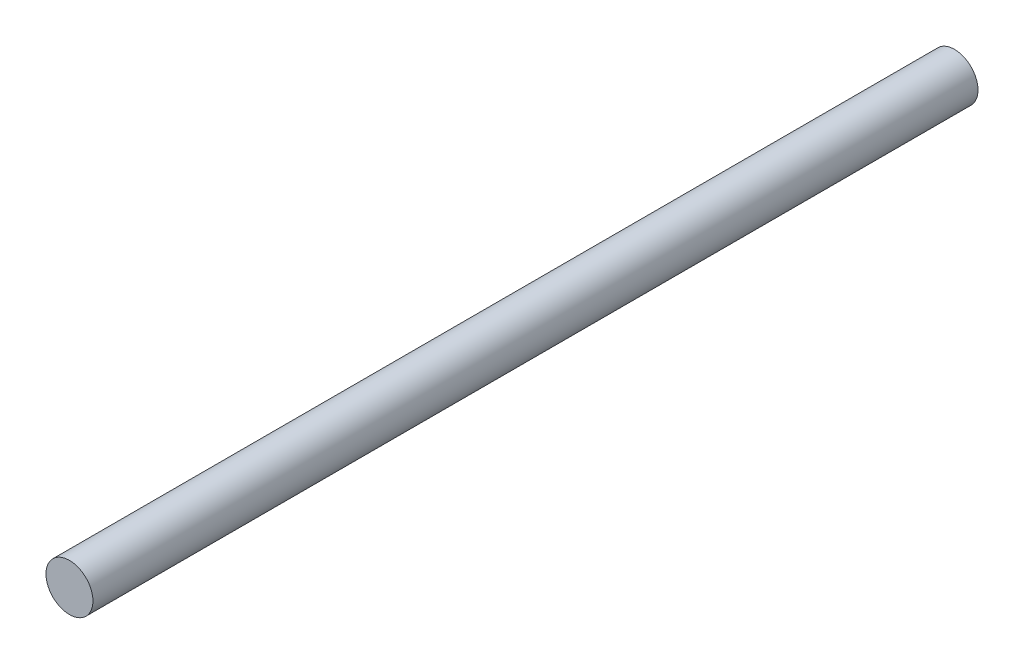
SolidWorks part; units mm, degrees
ref_plane "Front Plane" through (0, 0, 0) normal (0, 0, 1) x (1, 0, 0)
ref_plane "Top Plane" through (0, 0, 0) normal (0, 1, 0) x (1, 0, 0)
ref_plane "Right Plane" through (0, 0, 0) normal (1, 0, 0) x (0, 0, -1)
sketch "Sketch1" plane through (0, 0, 0) normal (0, 0, 1) x (1, 0, 0)
  circle A0 centre (0, 0) radius 11
  dimension "D1" = 22
extrude "Boss-Extrude1" add sketch "Sketch1" along normal blind 414.6
sketch "Sketch5" plane through (0, 0, 0) normal (0, 0, -1) x (-1, 0, 0)
  circle A0 centre (0, 0) radius 11
  dimension "D1" = 22
sketch "Sketch6" plane through (0, 0, 414.6) normal (0, 0, 1) x (1, 0, 0)
  circle A0 centre (0, 0) radius 11
